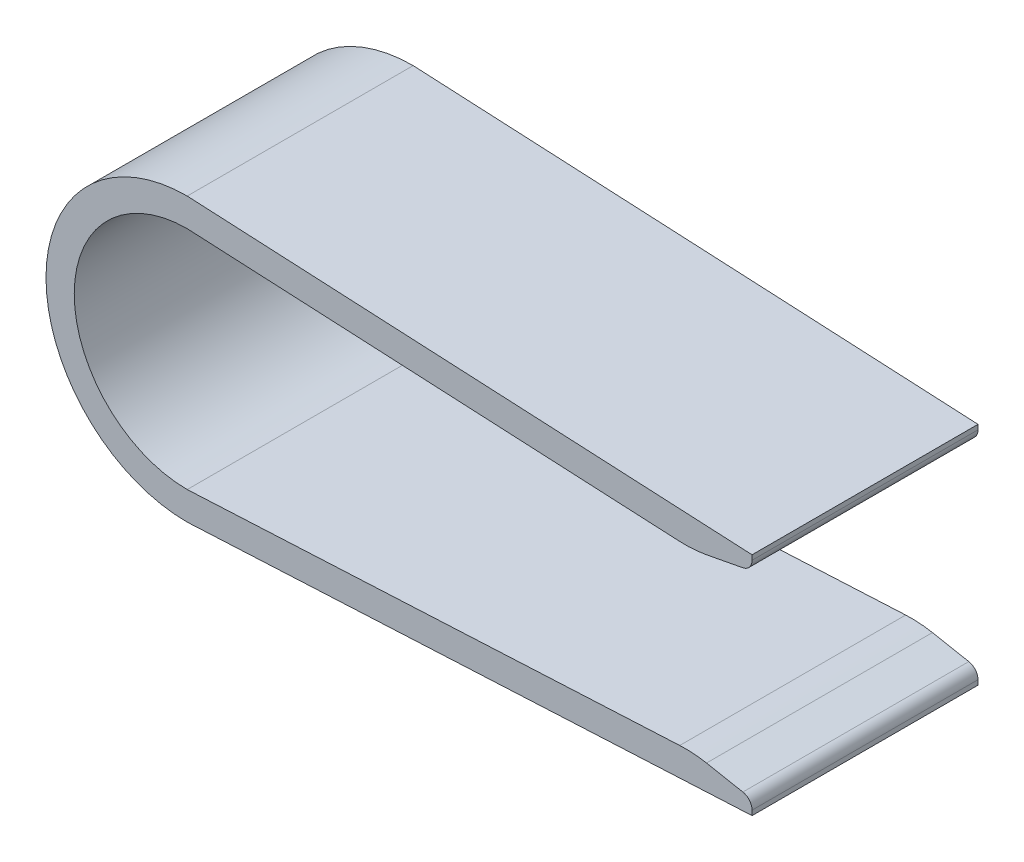
SolidWorks part; units mm, degrees
ref_plane "Front Plane" through (0, 0, 0) normal (0, 0, 1) x (1, 0, 0)
ref_plane "Top Plane" through (0, 0, 0) normal (0, 1, 0) x (1, 0, 0)
ref_plane "Right Plane" through (0, 0, 0) normal (1, 0, 0) x (0, 0, -1)
sketch "Sketch1" plane through (0, 0, 0) normal (0, 0, 1) x (1, 0, 0)
  line L6 (50, 10) -> (50, 8.75)
  line L7 (0, 10) -> (44.792, 7.7604)
  line L8 (0, -10) -> (44.792, -7.7604)
  line L9 (0, 12.5) -> (50, 10)
  line L10 (0, -12.5) -> (50, -10)
  line L11 (50, -8.75) -> (50, -10)
  line L12 (50, 8.75) -> (44.792, 7.7604)
  line L14 (44.792, -7.7604) -> (50, -8.75)
  arc A1 (0, 12.5) -> (0, -12.5) centre (0, 0) ccw
  arc A2 (0, 10) -> (0, -10) centre (0, 0) ccw
  dimension "D2" = 25
  dimension "D3" = 20
extrude "Boss-Extrude1" add sketch "Sketch1" along normal blind 20
fillet "Fillet1" radius 10 2 edges at (44.792, -7.7604, 10) (44.792, 7.7604, 10)
fillet "Fillet2" radius 1 2 edges at (50, -8.75, 10) (50, 8.75, 10)
